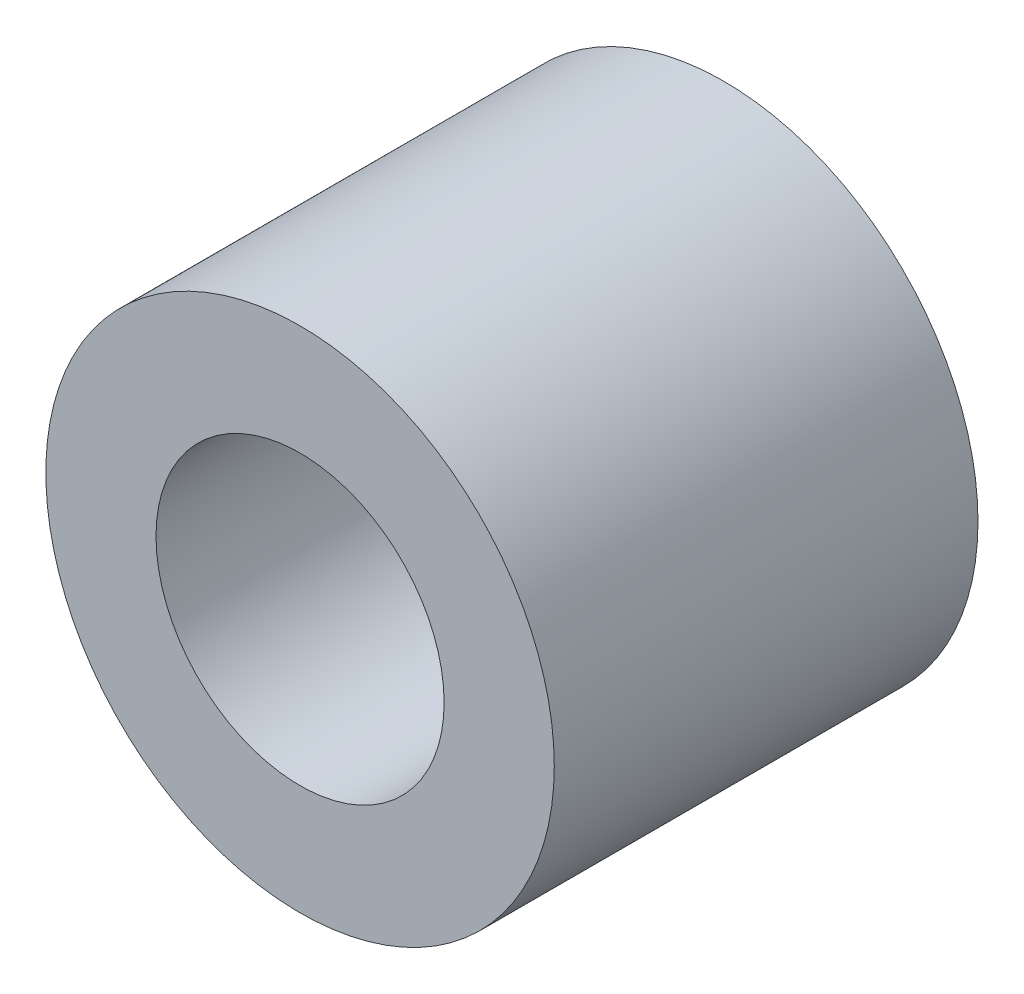
SolidWorks part; units mm, degrees
ref_plane "Front Plane" through (0, 0, 0) normal (0, 0, 1) x (1, 0, 0)
ref_plane "Top Plane" through (0, 0, 0) normal (0, 1, 0) x (1, 0, 0)
ref_plane "Right Plane" through (0, 0, 0) normal (1, 0, 0) x (0, 0, -1)
sketch "Sketch1" plane through (0, 0, 0) normal (0, 0, 1) x (1, 0, 0)
  circle A0 centre (0, 0) radius 3
  circle A1 centre (0, 0) radius 1.7
extrude "Boss-Extrude1" add sketch "Sketch1" against normal blind 5
